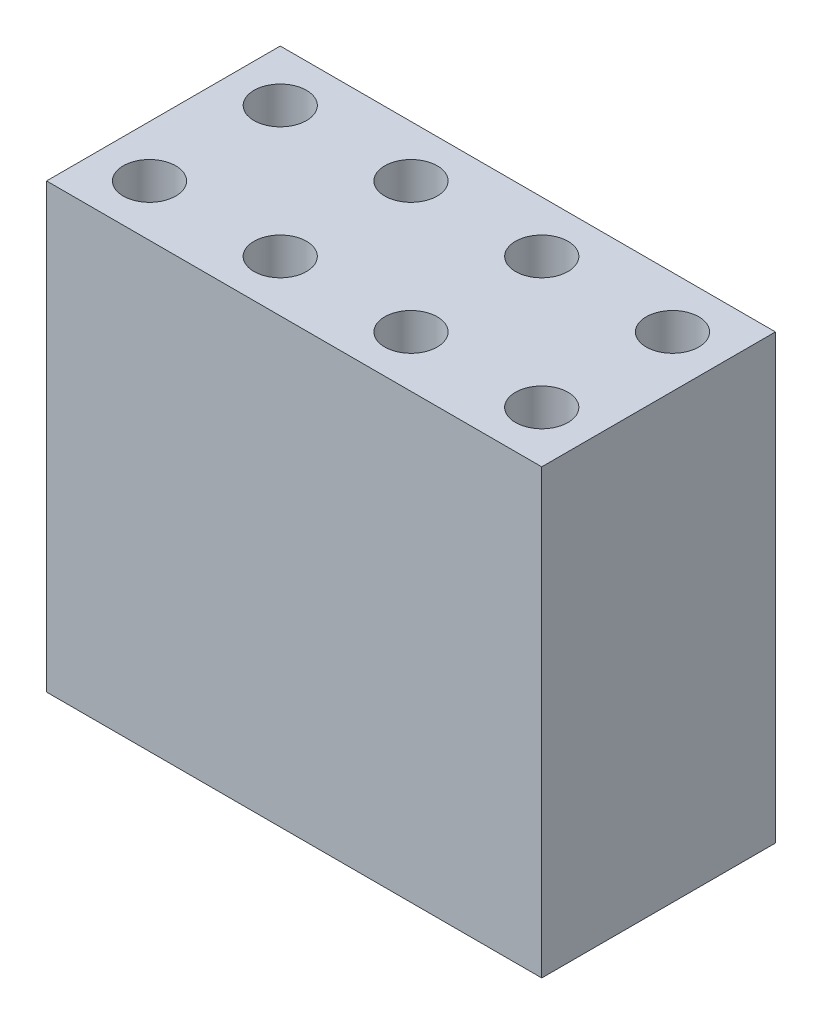
SolidWorks part; units mm, degrees
ref_plane "Plano frontal" through (0, 0, 0) normal (0, 0, 1) x (1, 0, 0)
ref_plane "Plano superior" through (0, 0, 0) normal (0, 1, 0) x (1, 0, 0)
ref_plane "Plano direito" through (0, 0, 0) normal (1, 0, 0) x (0, 0, -1)
sketch "Esboço2" plane through (0, 0, 0) normal (0, 1, 0) x (1, 0, 0)
  line L0 (0, 4.9048) -> (0, -4.5145) construction
  line L1 (-4.0469, 0) -> (5.9549, 0) construction
  line L3 (-3.81, 1.27) -> (3.81, 1.27) construction
  line L4 (-3.81, 1.27) -> (-3.81, -1.27) construction
  line L5 (-3.81, -1.27) -> (3.81, -1.27) construction
  line L6 (3.81, 1.27) -> (3.81, -1.27) construction
  line L7 (-3.81, 1.27) -> (3.81, -1.27) construction
  line L8 (-3.81, -1.27) -> (3.81, 1.27) construction
  line L9 (-4.81, 2.27) -> (4.81, 2.27)
  line L10 (-4.81, 2.27) -> (-4.81, -2.27)
  line L11 (-4.81, -2.27) -> (4.81, -2.27)
  line L12 (4.81, 2.27) -> (4.81, -2.27)
  line L13 (-4.81, 2.27) -> (4.81, -2.27) construction
  line L14 (-4.81, -2.27) -> (4.81, 2.27) construction
  circle A0 centre (-3.81, -1.27) radius 0.51
  circle A1 centre (-1.27, -1.27) radius 0.51
  circle A2 centre (1.27, -1.27) radius 0.51
  circle A3 centre (3.81, -1.27) radius 0.51
  circle A4 centre (3.81, 1.27) radius 0.51
  circle A5 centre (1.27, 1.27) radius 0.51
  circle A6 centre (-1.27, 1.27) radius 0.51
  circle A7 centre (-3.81, 1.27) radius 0.51
  point P5 (0, 0)
  point P24 (0, 0)
  dimension "D3" = 1.02
  dimension "D5" = 1
  dimension "D1" = 7.62
  dimension "D2" = 2.54
  dimension "D6" = 1
  dimension "D7" = 1
  dimension "D4" = 4
extrude "Ressalto-extrusão2" add sketch "Esboço2" along normal blind 8.6 contours L10 L9 L12 L11 | A7 | A1 | A5 | A4 | A3 | A2 | A6 | A0
